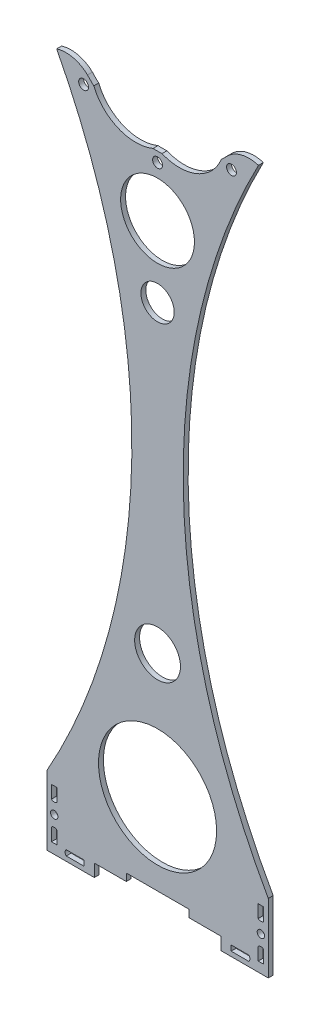
SolidWorks part; units mm, degrees
ref_plane "前视基准面" through (0, 0, 0) normal (0, 0, 1) x (1, 0, 0)
ref_plane "上视基准面" through (0, 0, 0) normal (0, 1, 0) x (1, 0, 0)
ref_plane "右视基准面" through (0, 0, 0) normal (1, 0, 0) x (0, 0, -1)
sketch "草图3" plane through (0, 0, 0) normal (0, 0, 1) x (1, 0, 0)
  line L0 (-45, -253.9902) -> (-45, -225.9902)
  line L11 (45, -253.9902) -> (45, -225.9902)
  line L103 (-37, -251.9902) -> (-37, -252.0902) construction
  line L104 (-41, -253.9902) -> (-42, -253.9902)
  line L110 (41, -253.9902) -> (45, -253.9902)
  line L111 (-37, -249.9902) -> (-30, -249.9902) construction
  line L114 (-37, -249.9902) -> (-37, -251.9902) construction
  line L115 (-37, -251.9902) -> (-30, -251.9902) construction
  line L116 (-30, -249.9902) -> (-30, -251.9902) construction
  line L117 (-37, -252.0902) -> (-37.1, -252.0902) construction
  line L118 (30, -249.9902) -> (37, -249.9902) construction
  line L119 (30, -249.9902) -> (30, -251.9902) construction
  line L120 (30, -251.9902) -> (37, -251.9902) construction
  line L121 (37, -249.9902) -> (37, -251.9902) construction
  line L122 (-37.1, -252.0902) -> (-29.9, -252.0902)
  line L123 (-37.1, -249.8902) -> (-29.9, -249.8902)
  line L124 (-29.9, -252.0902) -> (-29.9, -249.8902)
  line L125 (29.9, -252.0902) -> (29.9, -249.8902)
  line L139 (37.1, -252.0902) -> (29.9, -252.0902)
  line L142 (37.1, -249.8902) -> (29.9, -249.8902)
  line L143 (-25.7, -253.9902) -> (-25.7, -249.8902)
  line L144 (-41, -249.9902) -> (-44, -249.9902) construction
  line L151 (-44, -249.9902) -> (-44, -244.9902) construction
  line L152 (-44, -244.9902) -> (-41, -244.9902) construction
  line L153 (-41, -234.9902) -> (-44, -234.9902) construction
  line L154 (-44, -234.9902) -> (-44, -229.9902) construction
  line L155 (-44, -229.9902) -> (-41, -229.9902) construction
  line L156 (-41, -253.9902) -> (-25.7, -253.9902)
  line L157 (0, -239.4902) -> (0, -244.9902) construction
  line L158 (-25.7, -249.8902) -> (-25.7, -248.8902)
  line L159 (41, -253.9902) -> (25.7, -253.9902)
  line L160 (25.7, -249.8902) -> (25.7, -248.8902)
  line L161 (25.7, -253.9902) -> (25.7, -249.8902)
  line L162 (-25.7, -248.8902) -> (25.7, -248.8902) construction
  line L163 (-25.7, -248.8902) -> (-12.7, -248.8902)
  line L164 (25.7, -248.8902) -> (12.7, -248.8902)
  line L165 (-12.7, -248.8902) -> (-12.7, -245.8902)
  line L166 (-12.7, -245.8902) -> (12.7, -245.8902)
  line L167 (12.7, -245.8902) -> (12.7, -248.8902)
  line L168 (-42, -249.9902) -> (-42, -244.9902) construction
  line L169 (-42, -234.9902) -> (-42, -229.9902) construction
  line L170 (-43.1, -244.8902) -> (-43.1, -250.0902)
  line L171 (-43.1, -250.0902) -> (-40.9, -250.0902)
  line L172 (-40.9, -244.8902) -> (-40.9, -250.0902)
  line L173 (-43.1, -244.8902) -> (-40.9, -250.0902) construction
  line L174 (-43.1, -250.0902) -> (-40.9, -244.8902) construction
  line L176 (-43.1, -229.8902) -> (-43.1, -235.0902)
  line L177 (-40.9, -229.8902) -> (-40.9, -235.0902)
  line L178 (-43.1, -229.8902) -> (-40.9, -235.0902) construction
  line L179 (-43.1, -235.0902) -> (-40.9, -229.8902) construction
  line L181 (43.1, -235.0902) -> (40.9, -229.8902) construction
  line L182 (43.1, -229.8902) -> (40.9, -235.0902) construction
  line L183 (43.1, -250.0902) -> (40.9, -244.8902) construction
  line L184 (43.1, -244.8902) -> (40.9, -250.0902) construction
  line L185 (42, -234.9902) -> (42, -229.9902) construction
  line L186 (42, -249.9902) -> (42, -244.9902) construction
  line L187 (44, -229.9902) -> (41, -229.9902) construction
  line L188 (44, -234.9902) -> (44, -229.9902) construction
  line L189 (41, -234.9902) -> (44, -234.9902) construction
  line L190 (44, -244.9902) -> (41, -244.9902) construction
  line L191 (44, -249.9902) -> (44, -244.9902) construction
  line L192 (41, -249.9902) -> (44, -249.9902) construction
  line L193 (40.9, -229.8902) -> (40.9, -235.0902)
  line L194 (43.1, -229.8902) -> (43.1, -235.0902)
  line L195 (43.1, -229.8902) -> (40.9, -229.8902)
  line L196 (40.9, -244.8902) -> (40.9, -250.0902)
  line L197 (43.1, -250.0902) -> (40.9, -250.0902)
  line L198 (43.1, -244.8902) -> (43.1, -250.0902)
  line L199 (-42, -253.9902) -> (-44, -253.9902)
  line L200 (-44, -253.9902) -> (-45, -253.9902)
  line L202 (-43.1, -229.8902) -> (-40.9, -229.8902)
  line L205 (42, -234.9902) -> (42, -244.9902) construction
  circle A4 centre (0, 10.5098) radius 2
  circle A5 centre (-30.052, 22.9577) radius 2
  circle A11 centre (30.052, 22.9577) radius 2
  circle A13 centre (42.5, 53.0098) radius 2 [skipped]
  circle A14 centre (30.052, 83.0618) radius 2 [skipped]
  circle A15 centre (-30.052, 83.0618) radius 2 [skipped]
  circle A16 centre (0, 95.5098) radius 2 [skipped]
  arc A33 (-1.8118, 14.5524) -> (1.8098, 14.5523) centre (0, 53.0098) ccw
  arc A36 (1.8098, 14.5523) -> (25.9123, 24.5352) centre (8.8696, 31.5951) ccw
  arc A37 (-25.9138, 24.5366) -> (-1.8118, 14.5524) centre (-8.8707, 31.5955) ccw
  arc A74 (37.1, -249.8902) -> (37.1, -252.0902) centre (36, -250.9902) cw
  arc A75 (-37.1, -252.0902) -> (-37.1, -249.8902) centre (-36, -250.9902) cw
  arc A76 (-43.1, -244.8902) -> (-40.9, -244.8902) centre (-42, -245.9902) cw
  arc A77 (-43.1, -235.0902) -> (-40.9, -235.0902) centre (-42, -233.9902) ccw
  arc A78 (40.9, -235.0902) -> (43.1, -235.0902) centre (42, -233.9902) ccw
  arc A79 (40.9, -244.8902) -> (43.1, -244.8902) centre (42, -245.9902) cw
  circle A85 centre (42, -239.9902) radius 1.5
  circle A88 centre (-42, -239.9902) radius 1.5
  arc A92 (45, -225.9902) -> (41, 30.0098) centre (278.5199, -94.3102) cw
  arc A93 (-45, -225.9902) -> (-41, 30.0098) centre (-278.5199, -94.3102) ccw
  circle A95 centre (0, -212.7618) radius 24
  circle A96 centre (0, -9.975) radius 15
  circle A97 centre (0, -162.2509) radius 9.3005
  circle A99 centre (0, -38.8075) radius 6.764
  circle A100 centre (-42.5, 53.0098) radius 2 [skipped]
  circle A103 centre (0, 53.0098) radius 38.5 construction
  circle A104 centre (0, 53.0098) radius 42.5 construction
  arc A105 (25.9123, 24.5352) -> (28.4742, 27.0971) centre (0, 53.0098) ccw
  arc A107 (41, 30.0098) -> (28.4742, 27.0971) centre (37.1897, 18.0065) ccw
  arc A108 (-41, 30.0098) -> (-28.4742, 27.0971) centre (-37.1897, 18.0065) cw
  arc A110 (-25.9138, 24.5366) -> (-28.4742, 27.0971) centre (0.0001, 53.0099) cw
  point P90 (-42, -247.4902)
  point P114 (-42, -232.4902)
  point P178 (42, -232.4902)
  point P179 (42, -247.4902)
  dimension "D1" = 8
extrude "凸台-拉伸1" add sketch "草图3" along normal blind 2
